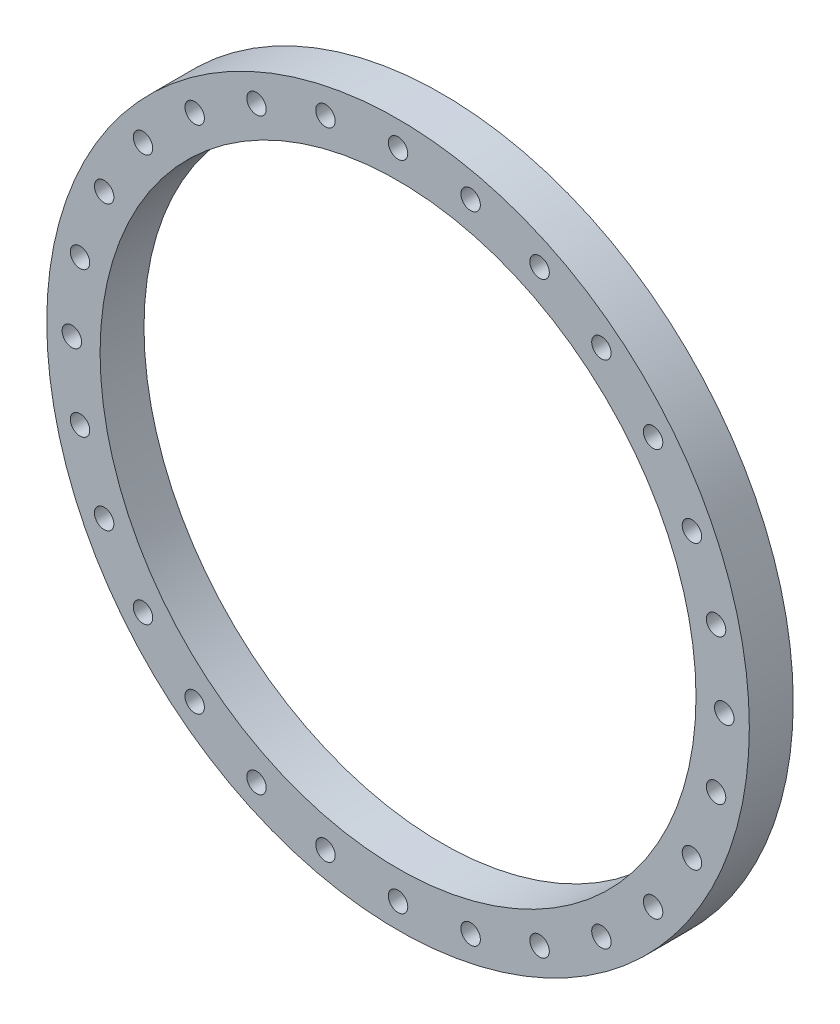
SolidWorks part; units mm, degrees
ref_plane "前视基准面" through (0, 0, 0) normal (0, 0, 1) x (1, 0, 0)
ref_plane "上视基准面" through (0, 0, 0) normal (0, 1, 0) x (1, 0, 0)
ref_plane "右视基准面" through (0, 0, 0) normal (1, 0, 0) x (0, 0, -1)
sketch "草图1" plane through (0, 0, 0) normal (0, 0, 1) x (1, 0, 0)
  circle A0 centre (0, 0) radius 47.5
  circle A1 centre (0, 0) radius 56
  circle A2 centre (0, 0) radius 52 construction
  circle A3 centre (0, 52) radius 1.55
  circle A4 centre (11.5711, 50.6963) radius 1.55
  circle A5 centre (22.562, 46.8504) radius 1.55
  circle A6 centre (32.4215, 40.6552) radius 1.55
  circle A7 centre (40.6552, 32.4215) radius 1.55
  circle A8 centre (46.8504, 22.562) radius 1.55
  circle A9 centre (50.6963, 11.5711) radius 1.55
  circle A10 centre (52, 0) radius 1.55
  circle A11 centre (50.6963, -11.5711) radius 1.55
  circle A12 centre (46.8504, -22.562) radius 1.55
  circle A13 centre (40.6552, -32.4215) radius 1.55
  circle A14 centre (32.4215, -40.6552) radius 1.55
  circle A15 centre (22.562, -46.8504) radius 1.55
  circle A16 centre (11.5711, -50.6963) radius 1.55
  circle A17 centre (0, -52) radius 1.55
  circle A18 centre (-11.5711, -50.6963) radius 1.55
  circle A19 centre (-22.562, -46.8504) radius 1.55
  circle A20 centre (-32.4215, -40.6552) radius 1.55
  circle A21 centre (-40.6552, -32.4215) radius 1.55
  circle A22 centre (-46.8504, -22.562) radius 1.55
  circle A23 centre (-50.6963, -11.5711) radius 1.55
  circle A24 centre (-52, 0) radius 1.55
  circle A25 centre (-50.6963, 11.5711) radius 1.55
  circle A26 centre (-46.8504, 22.562) radius 1.55
  circle A27 centre (-40.6552, 32.4215) radius 1.55
  circle A28 centre (-32.4215, 40.6552) radius 1.55
  circle A29 centre (-22.562, 46.8504) radius 1.55
  circle A30 centre (-11.5711, 50.6963) radius 1.55
  point P63 (0, 0)
  dimension "D1" = 95
  dimension "D2" = 112
  dimension "D3" = 104
  dimension "D4" = 3.1
  dimension "D5" = 28
extrude "凸台-拉伸1" add sketch "草图1" along normal blind 7
